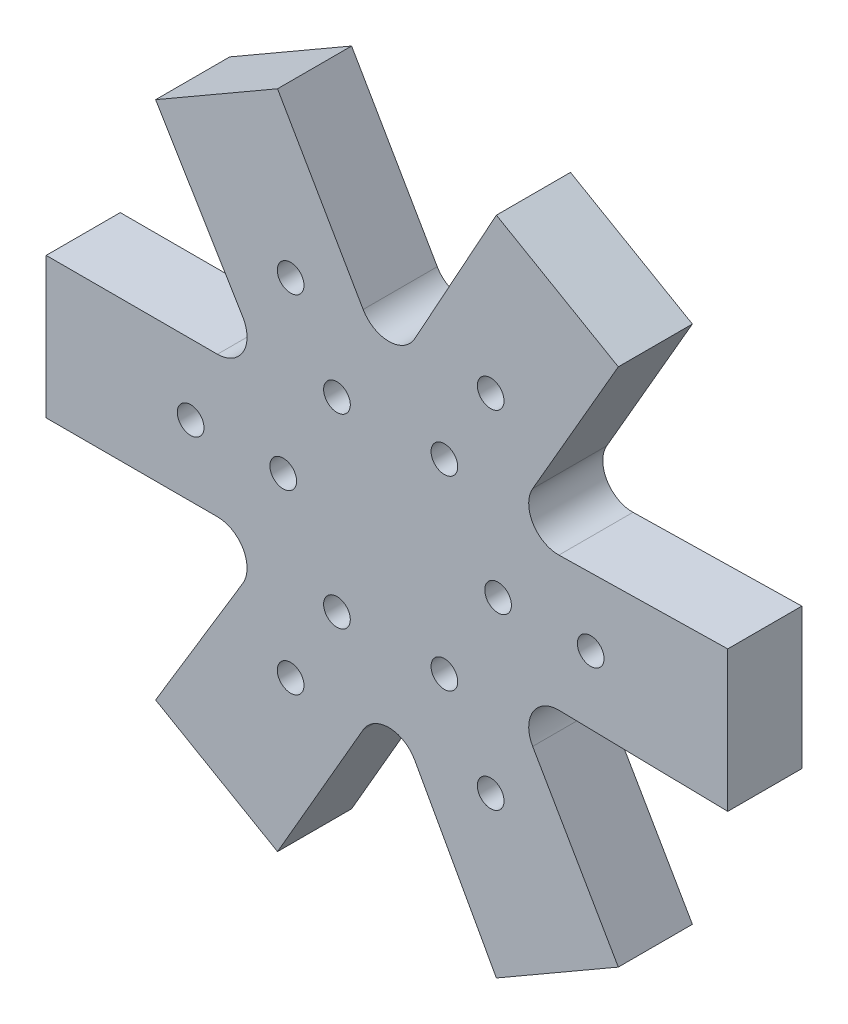
SolidWorks part; units mm, degrees
ref_plane "Front Plane" through (0, 0, 0) normal (0, 0, 1) x (1, 0, 0)
ref_plane "Top Plane" through (0, 0, 0) normal (0, 1, 0) x (1, 0, 0)
ref_plane "Right Plane" through (0, 0, 0) normal (1, 0, 0) x (0, 0, -1)
sketch "Sketch1" plane through (0, 0, 0) normal (0, 0, 1) x (1, 0, 0)
  line L4 (-23.25, 4.75) -> (-23.25, -4.75)
  line L5 (-7.6364, 22.2936) -> (-15.8636, 17.5436)
  line L8 (15.3636, 17.5436) -> (7.1364, 22.2936)
  line L11 (22.75, -4.75) -> (22.75, 4.75)
  line L14 (7.1364, -22.2936) -> (15.3636, -17.5436)
  line L17 (-15.8636, -17.5436) -> (-7.6364, -22.2936)
  line L18 (11.3543, 4.5339) -> (22.75, 4.75)
  line L19 (9.5843, 7.5335) -> (15.3636, 17.5436)
  line L20 (9.5843, -7.5335) -> (15.3636, -17.5436)
  line L21 (11.3543, -4.5339) -> (22.75, -4.75)
  line L22 (-1.8571, -12.2835) -> (-7.6364, -22.2936)
  line L23 (1.6257, -12.3165) -> (7.1364, -22.2936)
  line L24 (-11.6913, -4.75) -> (-23.25, -4.75)
  line L25 (-9.9786, -7.7827) -> (-15.8636, -17.5436)
  line L26 (-9.9786, 7.7827) -> (-15.8636, 17.5436)
  line L27 (-11.6913, 4.75) -> (-23.25, 4.75)
  line L28 (1.6257, 12.3165) -> (7.1364, 22.2936)
  line L29 (-1.8571, 12.2835) -> (-7.6364, 22.2936)
  arc A0 (11.3543, -4.5339) -> (9.5843, -7.5335) centre (11.3163, -6.5335) ccw
  arc A1 (1.6257, -12.3165) -> (-1.8571, -12.2835) centre (-0.125, -13.2835) ccw
  arc A2 (-9.9786, -7.7827) -> (-11.6913, -4.75) centre (-11.6913, -6.75) ccw
  arc A3 (-11.6913, 4.75) -> (-9.9786, 7.7827) centre (-11.6913, 6.75) ccw
  arc A4 (-1.8571, 12.2835) -> (1.6257, 12.3165) centre (-0.125, 13.2835) ccw
  arc A5 (9.5843, 7.5335) -> (11.3543, 4.5339) centre (11.3163, 6.5335) ccw
  point P2 (0, 0)
  point P6 (0, 0)
  point P7 (0, 0)
  point P11 (0, 0)
  point P12 (0, 0)
  dimension "D1" = 2
  dimension "D2" = 9.5
  dimension "D3" = 6
  dimension "D4" = 46
extrude "Boss-Extrude2" add sketch "Sketch1" along normal blind 5
sketch "Sketch7" plane through (0, 0, 0) normal (0, 0, -1) x (-1, 0, 0)
  line L0 (0, 0) -> (17.325, 0) construction
  line L1 (14.575, 0) -> (14.575, 2.5) construction
  line L14 (-6.859, 3.9601) -> (-9.8493, 11.6226)
  line L15 (-6.859, 3.9601) -> (-14.9901, 2.7185)
  line L16 (0, 7.9201) -> (5.1408, 14.341)
  line L17 (0, 7.9201) -> (-5.1408, 14.341)
  line L18 (6.859, 3.9601) -> (14.9901, 2.7185)
  line L19 (6.859, 3.9601) -> (9.8493, 11.6226)
  line L20 (6.859, -3.9601) -> (9.8493, -11.6226)
  line L21 (6.859, -3.9601) -> (14.9901, -2.7185)
  line L22 (0, -7.9201) -> (-5.1408, -14.341)
  line L23 (0, -7.9201) -> (5.1408, -14.341)
  line L24 (-6.859, -3.9601) -> (-14.9901, -2.7185)
  line L25 (-6.859, -3.9601) -> (-9.8493, -11.6226)
  circle A0 centre (0, 0) radius 4.75 construction
  arc A1 (14.9901, 2.7185) -> (14.9901, -2.7185) centre (14.575, 0) cw
  arc A2 (9.8493, -11.6226) -> (5.1408, -14.341) centre (7.2875, -12.6223) cw
  arc A3 (-5.1408, -14.341) -> (-9.8493, -11.6226) centre (-7.2875, -12.6223) cw
  arc A4 (-14.9901, -2.7185) -> (-14.9901, 2.7185) centre (-14.575, 0) cw
  arc A5 (-9.8493, 11.6226) -> (-5.1408, 14.341) centre (-7.2875, 12.6223) cw
  arc A6 (5.1408, 14.341) -> (9.8493, 11.6226) centre (7.2875, 12.6223) cw
  point P37 (0, 0)
  dimension "D4" = 9.5
  dimension "D2" = 2.5
extrude "Cut-Extrude5" cut sketch "Sketch7" against normal blind 2.5
sketch "Sketch8" plane through (0, 0, 2.5) normal (0, 0, -1) x (-1, 0, 0)
  line L0 (0, 0) -> (17.325, 0) construction
  arc A0 (14.9901, -2.7185) -> (14.9901, 2.7185) centre (14.575, 0) ccw construction
  circle A1 centre (7.25, 0) radius 0.9
  circle A2 centre (13.5, 0) radius 0.9
  circle A3 centre (6.75, -11.6913) radius 0.9
  circle A4 centre (3.625, -6.2787) radius 0.9
  circle A5 centre (-6.75, -11.6913) radius 0.9
  circle A6 centre (-3.625, -6.2787) radius 0.9
  circle A7 centre (-13.5, 0) radius 0.9
  circle A8 centre (-7.25, 0) radius 0.9
  circle A9 centre (-6.75, 11.6913) radius 0.9
  circle A10 centre (-3.625, 6.2787) radius 0.9
  circle A11 centre (6.75, 11.6913) radius 0.9
  circle A12 centre (3.625, 6.2787) radius 0.9
  point P32 (0, 0)
  dimension "D2" = 1.8
  dimension "D4" = 1.8
  dimension "D1" = 7.25
  dimension "D3" = 13.5
extrude "Cut-Extrude6" cut sketch "Sketch8" against normal through all
